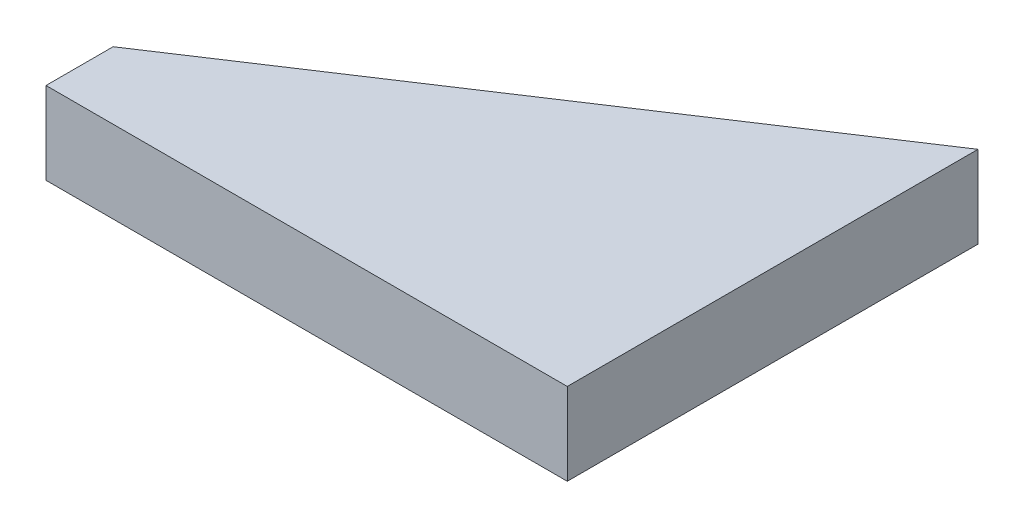
SolidWorks part; units mm, degrees
ref_plane "Front Plane" through (0, 0, 0) normal (0, 0, 1) x (1, 0, 0)
ref_plane "Top Plane" through (0, 0, 0) normal (0, 1, 0) x (1, 0, 0)
ref_plane "Right Plane" through (0, 0, 0) normal (1, 0, 0) x (0, 0, -1)
sketch "Sketch1" plane through (0, 0, 0) normal (0, 1, 0) x (1, 0, 0)
  line L0 (12.4, 0) -> (75.8578, 0)
  line L1 (75.8578, 0) -> (75.8578, 50)
  line L2 (75.8578, 50) -> (12.4, 8.1732)
  line L3 (0, 0) -> (0, -2.553) construction
  line L4 (0, -2.553) -> (12.4, -2.553) construction
  line L5 (12.4, 0) -> (12.4, 8.1732)
  dimension "D1" = 33.39
  dimension "D2" = 50
  dimension "D3" = 12.4
extrude "Boss-Extrude1" add sketch "Sketch1" along normal blind 10
